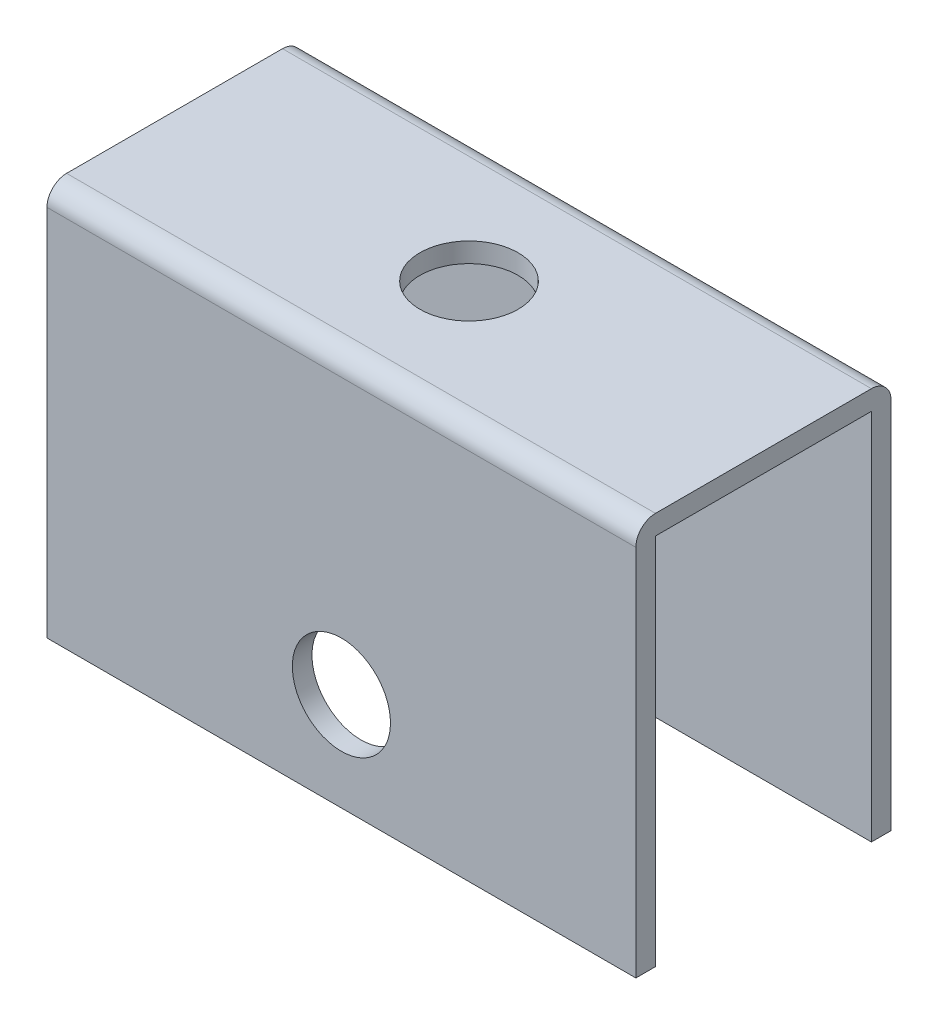
SolidWorks part; units mm, degrees
material "Plain Carbon Steel"
ref_plane "Front Plane" through (0, 0, 0) normal (0, 0, 1) x (1, 0, 0)
ref_plane "Top Plane" through (0, 0, 0) normal (0, 1, 0) x (1, 0, 0)
ref_plane "Right Plane" through (0, 0, 0) normal (1, 0, 0) x (0, 0, -1)
sketch "Sketch1" plane through (0, 0, 0) normal (0, 0, 1) x (1, 0, 0)
  line L1 (-38.1, 25.4) -> (38.1, 25.4)
  line L2 (-38.1, 25.4) -> (-38.1, -25.4)
  line L3 (-38.1, -25.4) -> (38.1, -25.4)
  line L4 (38.1, 25.4) -> (38.1, -25.4)
  line L5 (-38.1, 25.4) -> (38.1, -25.4) construction
  line L6 (-38.1, -25.4) -> (38.1, 25.4) construction
  circle A0 centre (0, -12.7) radius 6.35
  point P0 (0, 0)
  dimension "D3" = 12.7
  dimension "D4" = 12.7
  dimension "D1" = 76.2
  dimension "D2" = 50.8
extrude "Boss-Extrude1" add sketch "Sketch1" along normal blind 33.02
sketch "Sketch2" plane through (38.1, 0, 0) normal (1, 0, 0) x (0, 0, -1)
  line L4 (-30.48, -38.1) -> (-2.54, -38.1)
  line L8 (-2.54, -22.86) -> (-2.54, 22.86)
  line L9 (-2.54, 22.86) -> (-30.48, 22.86)
  line L10 (-30.48, 22.86) -> (-30.48, -22.86)
  line L11 (-30.48, -22.86) -> (-2.54, -22.86)
  line L12 (-2.54, -38.1) -> (-2.54, 22.86)
  line L13 (-2.54, 22.86) -> (-30.48, 22.86)
  line L14 (-30.48, 22.86) -> (-30.48, -38.1)
  dimension "D1" = 2.54
extrude "Cut-Extrude1" cut sketch "Sketch2" against normal through all
sketch "Sketch3" plane through (0, 22.86, 0) normal (0, -1, 0) x (1, 0, 0)
  circle A0 centre (0, 16.51) radius 6.35
  dimension "D1" = 12.7
extrude "Cut-Extrude2" cut sketch "Sketch3" against normal through all
fillet "Fillet1" radius 2.54 2 edges at (0, 25.4, 0) (0, 25.4, 33.02)
